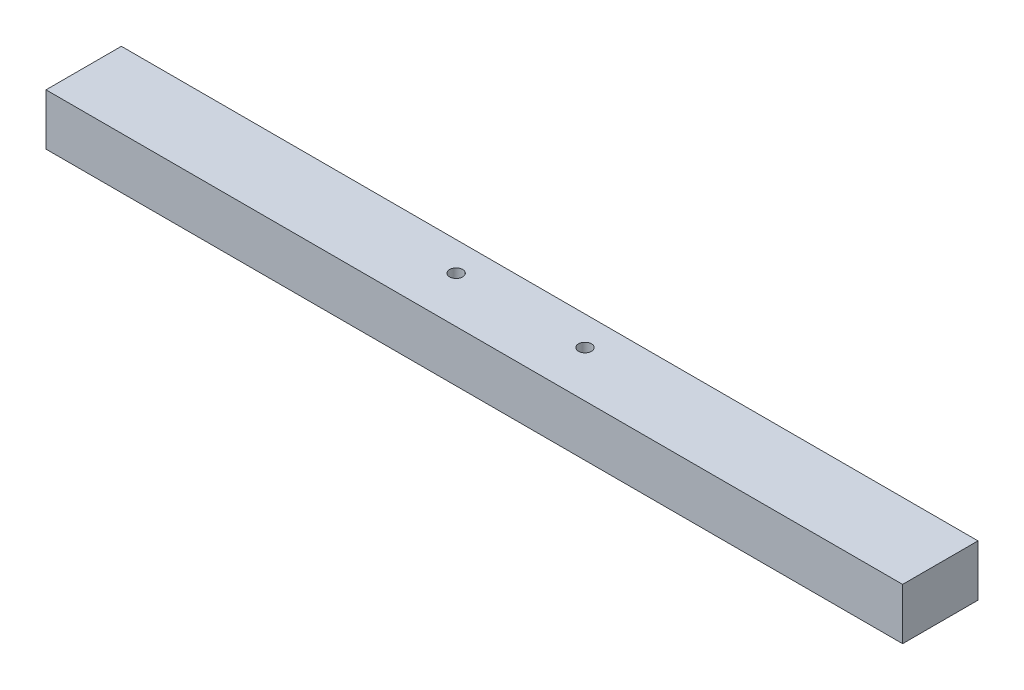
SolidWorks part; units mm, degrees
ref_plane "Alzado" through (0, 0, 0) normal (0, 0, 1) x (1, 0, 0)
ref_plane "Planta" through (0, 0, 0) normal (0, 1, 0) x (1, 0, 0)
ref_plane "Vista lateral" through (0, 0, 0) normal (1, 0, 0) x (0, 0, -1)
sketch "Croquis1" plane through (0, 0, 0) normal (0, 1, 0) x (1, 0, 0)
  line L0 (0, 2.5) -> (-18.8, 2.5) construction
  line L1 (125, -11) -> (-125, -11)
  line L2 (125, -11) -> (125, 11)
  line L3 (125, 11) -> (-125, 11)
  line L4 (-125, -11) -> (-125, 11)
  line L5 (125, -11) -> (-125, 11) construction
  line L6 (125, 11) -> (-125, -11) construction
  line L7 (0, 2.5) -> (18.8, 2.5) construction
  circle A0 centre (-18.8, 2.5) radius 1.9
  circle A1 centre (18.8, 2.5) radius 1.9
  point P0 (0, 0)
  dimension "D3" = 3.8
  dimension "D1" = 22
  dimension "D2" = 250
  dimension "D4" = 18.8
  dimension "D5" = 8.5
extrude "Saliente-Extruir1" add sketch "Croquis1" along normal blind 15
sketch "Croquis2" plane through (0, 15, 0) normal (0, 1, 0) x (1, 0, 0)
  line L0 (-125, 0) -> (125, 0) construction
  line L1 (-125, 11) -> (-125, -11) construction
  line L2 (125, -11) -> (125, 11) construction
